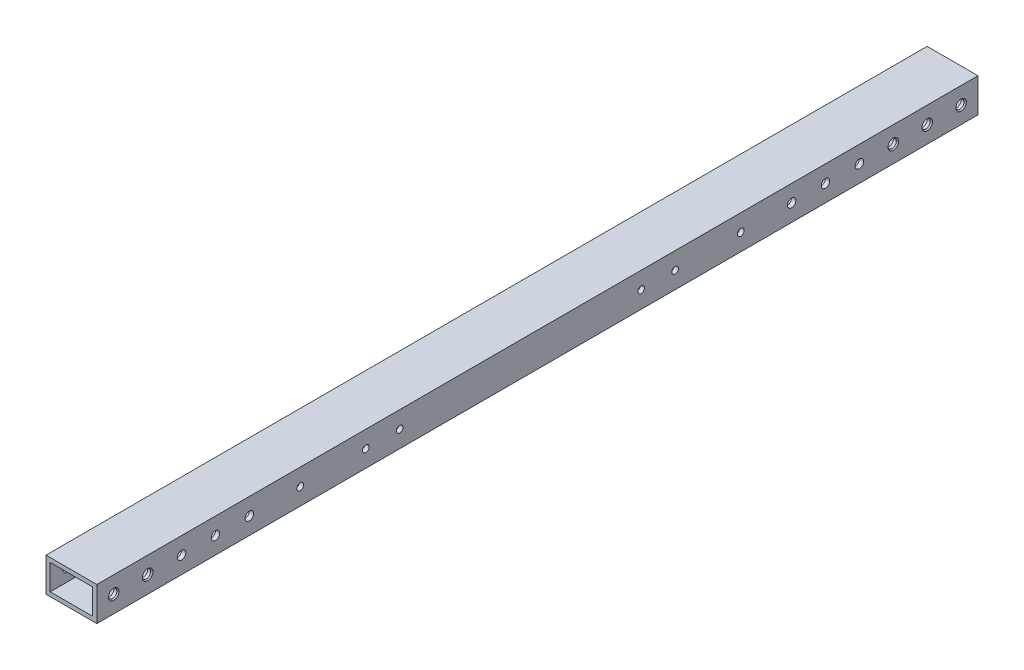
SolidWorks part; units mm, degrees
ref_plane "Front Plane" through (0, 0, 0) normal (0, 0, 1) x (1, 0, 0)
ref_plane "Top Plane" through (0, 0, 0) normal (0, 1, 0) x (1, 0, 0)
ref_plane "Right Plane" through (0, 0, 0) normal (1, 0, 0) x (0, 0, -1)
sketch "Sketch1" plane through (0, 0, 0) normal (0, 0, 1) x (1, 0, 0)
  line L0 (-15.875, 9.525) -> (15.875, 9.525)
  line L2 (-19.05, 12.7) -> (19.05, 12.7)
  line L3 (-19.05, 12.7) -> (-19.05, -12.7)
  line L4 (-19.05, -12.7) -> (19.05, -12.7)
  line L5 (19.05, 12.7) -> (19.05, -12.7)
  line L10 (15.875, 9.525) -> (15.875, -9.525)
  line L11 (-15.875, -9.525) -> (15.875, -9.525)
  line L12 (-15.875, 9.525) -> (-15.875, -9.525)
  point P12 (0, 12.7)
  point P14 (19.05, 0)
  dimension "Wall Thickness" = 3.175
  dimension "Outside Width" = 38.1
  dimension "Outside Height" = 25.4
  dimension "Inside Height" = 19.05
  dimension "Inside Width" = 31.75
sketch "Sketch2" plane through (0, 0, 0) normal (1, 0, 0) x (0, 0, -1)
  line L0 (330.2, 0) -> (-330.2, 0)
  point P4 (0, 0)
  point P7 (-330.2, 0)
  point P10 (330.2, 0)
  dimension "Length" = 660.4
sketch "Sketch3" plane through (0, 0, 0) normal (0, 0, 1) x (1, 0, 0)
  line L21 (19.05, 12.7) -> (-19.05, 12.7)
  line L22 (19.05, -12.7) -> (19.05, 12.7)
  line L23 (-19.05, -12.7) -> (19.05, -12.7)
  line L24 (-19.05, 12.7) -> (-19.05, -12.7)
  line L25 (19.05, 12.7) -> (-19.05, 12.7)
  line L26 (19.05, -12.7) -> (19.05, 12.7)
  line L27 (-19.05, -12.7) -> (19.05, -12.7)
  line L28 (-19.05, 12.7) -> (-19.05, -12.7)
  line L29 (15.875, 9.525) -> (-15.875, 9.525)
  line L30 (15.875, -9.525) -> (15.875, 9.525)
  line L31 (-15.875, -9.525) -> (15.875, -9.525)
  line L32 (-15.875, 9.525) -> (-15.875, -9.525)
  line L33 (15.875, 9.525) -> (-15.875, 9.525)
  line L34 (15.875, -9.525) -> (15.875, 9.525)
  line L35 (-15.875, -9.525) -> (15.875, -9.525)
  line L36 (-15.875, 9.525) -> (-15.875, -9.525)
  dimension "D1" = 0
  dimension "D2" = 0
extrude "Boss-Extrude1" add sketch "Sketch3" along normal up to vertex (330.2 mm away) and the other way up to vertex (330.2 mm away) up to point (0, 0, 330.2) other way up to point (0, 0, -330.2)
sketch "Drawing Reference" plane through (0, 0, 0) normal (1, 0, 0) x (0, 0, -1)
  line L0 (-330.2, 0) -> (330.2, 0) construction
  line L1 (0, -12.7) -> (0, 12.7) construction
  line L2 (-330.2, -12.7) -> (330.2, -12.7) construction
  line L5 (-330.2, 12.7) -> (330.2, 12.7) construction
  point P7 (-302.768, 0)
  point P8 (302.768, 0)
  dimension "D1" = 27.432
sketch "Sketch4" plane through (-19.05, 0, 0) normal (-1, 0, 0) x (0, 0, 1)
  line L0 (-330.2, 0) -> (-317.5, 0)
  line L1 (-330.2, 12.7) -> (-330.2, -12.7) construction
  line L2 (-317.5, 0) -> (-292.1, 0)
  line L3 (-292.1, 0) -> (-266.7, 0)
  line L4 (-266.7, 0) -> (-241.3, 0)
  line L5 (-241.3, 0) -> (-215.9, 0)
  line L6 (-215.9, 0) -> (-190.5, 0)
  line L7 (330.2, 0) -> (317.5, 0)
  line L8 (330.2, 12.7) -> (330.2, -12.7) construction
  line L9 (317.5, 0) -> (292.1, 0)
  line L10 (292.1, 0) -> (266.7, 0)
  line L11 (266.7, 0) -> (241.3, 0)
  line L12 (241.3, 0) -> (215.9, 0)
hole_wizard "1/4 (0.25) Diameter Hole2" positions "Sketch7" profile "Sketch8" hole size "1/4" standard "ANSI Inch" end condition through all
sketch "Sketch7" plane through (-19.05, 0, 0) normal (-1, 0, 0) x (0, 0, 1)
  point P0 (-317.5, 0)
  point P3 (-292.1, 0)
  point P7 (317.5, 0)
  point P11 (-266.7, 0)
  point P14 (292.1, 0)
sketch "Sketch8" plane through (-19.05, 0, -317.5) normal (0, 1, 0) x (0, 0, 1)
  line L0 (0, 0) -> (0, 38.1)
  line L1 (0, 38.1) -> (3.9624, 38.1)
  line L2 (3.175, 37.1942) -> (3.175, 0)
  line L5 (3.175, 0) -> (0, 0)
  line L7 (3.9624, 38.1) -> (3.175, 37.1942)
  line L8 (-3.9624, 38.1) -> (-3.175, 37.1942) construction
  line L11 (0, -6.35) -> (0, 107.95) construction
  dimension "Thru Hole Dia." = 6.35
  dimension "Thru Hole Depth" = 38.1
  dimension "Far C'Sink Dia." = 7.9248
  dimension "Far C'Sink Angle" = 82
hole_wizard "1/4 (0.25) Diameter Hole3" positions "Sketch9" profile "Sketch10" hole size "1/4" standard "ANSI Inch" end condition through all
sketch "Sketch9" plane through (19.05, 0, 0) normal (1, 0, 0) x (0, 0, -1)
  point P0 (-266.7, 0)
  point P3 (-241.3, 0)
  point P6 (-215.9, 0)
  point P9 (241.3, 0)
  point P12 (215.9, 0)
  point P15 (190.5, 0)
sketch "Sketch10" plane through (19.05, 0, 266.7) normal (0, 1, 0) x (0, 0, -1)
  line L0 (0, 0) -> (0, 38.1)
  line L1 (0, 38.1) -> (3.175, 38.1)
  line L2 (3.175, 38.1) -> (3.175, 0)
  line L5 (3.175, 0) -> (0, 0)
  line L11 (0, -6.35) -> (0, 107.95) construction
  dimension "Thru Hole Dia." = 6.35
  dimension "Thru Hole Depth" = 38.1
hole_wizard "13/64 (0.20313) Diameter Hole1" positions "Sketch11" profile "Sketch12" hole size "13/64" standard "ANSI Inch" end condition through all
sketch "Sketch11" plane through (19.05, 0, 0) normal (1, 0, 0) x (0, 0, -1)
  point P0 (152.4, 0)
  point P9 (-177.8, 0)
sketch "Sketch12" plane through (19.05, 0, -152.4) normal (0, 1, 0) x (0, 0, -1)
  line L0 (0, 0) -> (0, 38.1)
  line L1 (0, 38.1) -> (2.5798, 38.1)
  line L2 (2.5798, 38.1) -> (2.5798, 0)
  line L5 (2.5798, 0) -> (0, 0)
  line L11 (0, -6.35) -> (0, 107.95) construction
  dimension "Thru Hole Dia." = 5.1595
  dimension "Thru Hole Depth" = 38.1
sketch "Sketch13" plane through (19.05, 0, 0) normal (1, 0, 0) x (0, 0, -1)
  line L1 (77.7875, 0) -> (102.8316, 0)
hole_wizard "#10 Clearance Hole1" positions "Sketch14" profile "Sketch15" hole size "#10" standard "ANSI Inch" end condition through all
sketch "Sketch14" plane through (19.05, 0, 0) normal (1, 0, 0) x (0, 0, -1)
  point P19 (-128.5875, 0)
  point P22 (-103.1875, 0)
  point P35 (77.7875, 0)
  point P38 (103.1875, 0)
sketch "Sketch15" plane through (19.05, 0, 128.5875) normal (0, 1, 0) x (0, 0, -1)
  line L0 (0, 0) -> (0, 38.1)
  line L1 (0, 38.1) -> (2.4892, 38.1)
  line L2 (2.4892, 38.1) -> (2.4892, 0)
  line L5 (2.4892, 0) -> (0, 0)
  line L11 (0, -6.35) -> (0, 107.95) construction
  dimension "Thru Hole Dia." = 4.9784
  dimension "Thru Hole Depth" = 38.1
equation "\"D1@Drawing Reference\"=\"Outside Width@Sketch1\" * 0.72"
